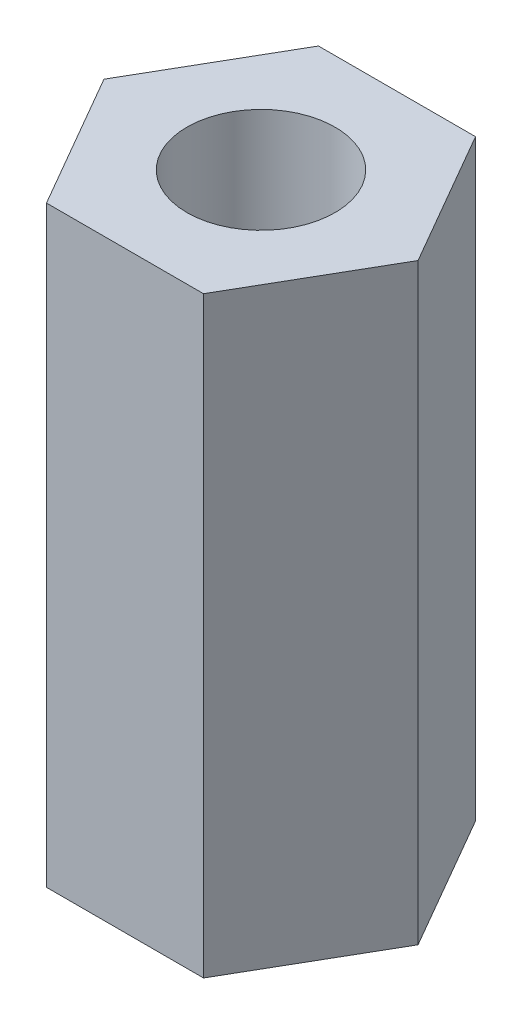
SolidWorks part; units mm, degrees
ref_plane "Front Plane" through (0, 0, 0) normal (0, 0, 1) x (1, 0, 0)
ref_plane "Top Plane" through (0, 0, 0) normal (0, 1, 0) x (1, 0, 0)
ref_plane "Right Plane" through (0, 0, 0) normal (1, 0, 0) x (0, 0, -1)
sketch "Sketch1" plane through (0, 0, 0) normal (0, 1, 0) x (1, 0, 0)
  line L1 (2.65, 0) -> (1.325, 2.295)
  line L2 (1.325, 2.295) -> (-1.325, 2.295)
  line L3 (-1.325, 2.295) -> (-2.65, 0)
  line L4 (-2.65, 0) -> (-1.325, -2.295)
  line L5 (-1.325, -2.295) -> (1.325, -2.295)
  line L6 (1.325, -2.295) -> (2.65, 0)
  circle A0 centre (0, 0) radius 2.65 construction
  circle A1 centre (0, 0) radius 2.295 construction
  dimension "D1" = 5.3
extrude "Boss-Extrude1" add sketch "Sketch1" along normal blind 10
ref_point "Point1"
hole_wizard "Tap Drill for M3 Tap1" positions "Sketch2" profile "Sketch4" hole size "M3" standard "ISO" end condition through all
sketch "Sketch2" plane through (0, 10, 0) normal (0, 1, 0) x (1, 0, 0)
  point P0 (0, 0)
sketch "Sketch4" plane through (0, 10, 0) normal (1, 0, 0) x (0, 0, 1)
  line L0 (0, 0) -> (0, 10)
  line L1 (0, 10) -> (1.25, 10)
  line L2 (1.25, 10) -> (1.25, 0)
  line L5 (1.25, 0) -> (0, 0)
  line L11 (0, -6.35) -> (0, 107.95) construction
  dimension "Thru Hole Dia." = 2.5
  dimension "Thru Hole Depth" = 10
